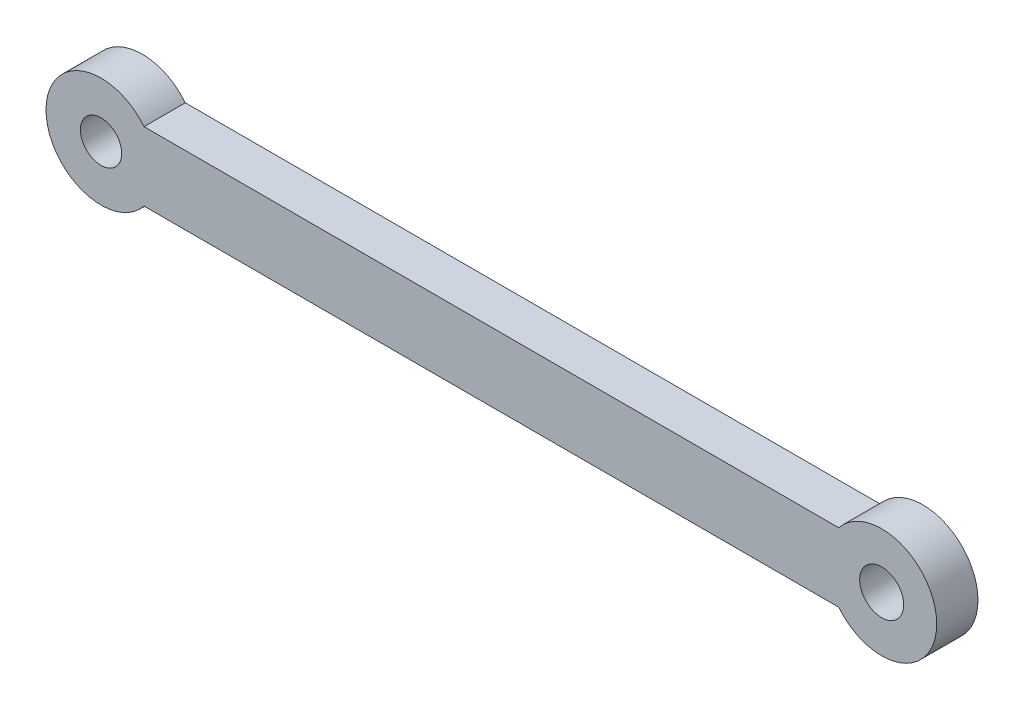
SolidWorks part; units mm, degrees
ref_plane "Front Plane" through (0, 0, 0) normal (0, 0, 1) x (1, 0, 0)
ref_plane "Top Plane" through (0, 0, 0) normal (0, 1, 0) x (1, 0, 0)
ref_plane "Right Plane" through (0, 0, 0) normal (1, 0, 0) x (0, 0, -1)
sketch "Sketch1" plane through (0, 0, 0) normal (0, 0, 1) x (1, 0, 0)
  line L0 (0, 0) -> (0, -18.1099) construction
  line L1 (-26.8775, -2.5) -> (30, -2.5)
  line L3 (-26.8775, 2.5) -> (30, 2.5)
  line L4 (30, -2.5) -> (30, 2.5)
  arc A0 (-26.8775, 2.5) -> (-26.8775, -2.5) centre (-30, 0) ccw
  circle A1 centre (-30, 0) radius 1.5
  point P0 (0, 0)
  dimension "D2" = 8
  dimension "D5" = 30
  dimension "D6" = 3
  dimension "D1" = 30
  dimension "D3" = 5
  dimension "D4" = 2.5
  dimension "D7" = 30
extrude "Boss-Extrude1" add sketch "Sketch1" along normal blind 3
sketch "Sketch2" plane through (0, 0, 3) normal (0, 0, 1) x (1, 0, 0)
  line L0 (-30, 0) -> (30, 0) construction
  line L1 (30, -2.5) -> (30, 2.5) construction
sketch "Sketch3" plane through (0, 0, 3) normal (0, 0, 1) x (1, 0, 0)
  circle A0 centre (26.7277, 0) radius 1.6
extrude "Cut-Extrude1" cut sketch "Sketch3" against normal blind 3
sketch "Sketch4" plane through (0, 0, 3) normal (0, 0, 1) x (1, 0, 0)
  circle A0 centre (26.7277, 0) radius 4
  circle A1 centre (26.7277, 0) radius 1.6 construction
  circle A2 centre (26.7277, 0) radius 1.6
  dimension "D1" = 8
extrude "Boss-Extrude2" add sketch "Sketch4" against normal blind 3
sketch "Sketch5" plane through (0, 0, 3) normal (0, 0, 1) x (1, 0, 0)
  line L0 (30, 2.5) -> (29.8502, 2.5) construction
  line L1 (30, 2.5) -> (29.8502, 2.5)
  line L2 (30, 2.3005) -> (30, 2.5) construction
  line L3 (30, 2.3005) -> (30, 2.5)
  line L4 (30, -2.5) -> (30, -2.3005) construction
  line L5 (30, -2.5) -> (30, -2.3005)
  line L6 (29.8502, -2.5) -> (30, -2.5) construction
  line L7 (29.8502, -2.5) -> (30, -2.5)
  arc A0 (29.8502, -2.5) -> (30, -2.3005) centre (26.7277, 0) ccw
  arc A1 (30, 2.3005) -> (29.8502, 2.5) centre (26.7277, 0) ccw
extrude "Cut-Extrude2" cut sketch "Sketch5" against normal blind 3
